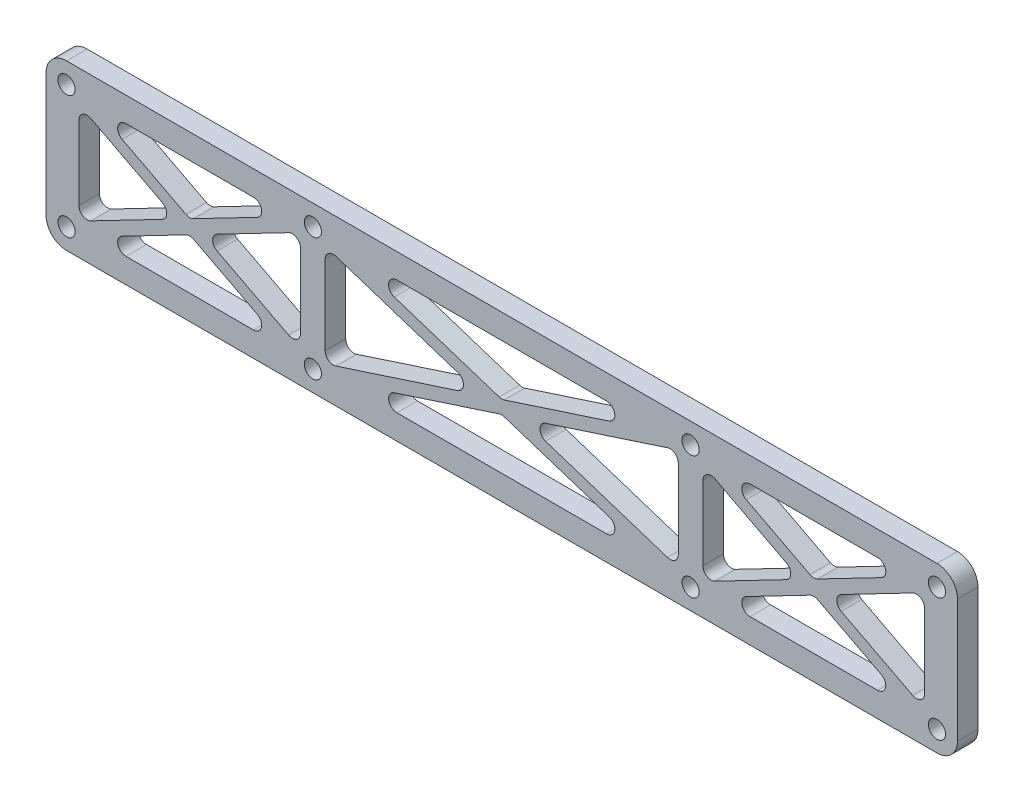
SolidWorks part; units mm, degrees
material "Thornel Mat VMA"
ref_plane "前视基准面" through (0, 0, 0) normal (0, 0, 1) x (1, 0, 0)
ref_plane "上视基准面" through (0, 0, 0) normal (0, 1, 0) x (1, 0, 0)
ref_plane "右视基准面" through (0, 0, 0) normal (1, 0, 0) x (0, 0, -1)
other "Configuration Table"
sketch "草图1" plane through (0, 0, 0) normal (0, 0, 1) x (1, 0, 0)
  line L1 (-116, -20) -> (116, -20)
  line L2 (-116, -20) -> (-116, 20)
  line L3 (-116, 20) -> (116, 20)
  line L4 (116, -20) -> (116, 20)
  line L5 (-116, -20) -> (116, 20) construction
  line L6 (-116, 20) -> (116, -20) construction
  line L7 (-46, -15) -> (46, -15) construction
  line L8 (-46, -15) -> (-46, 15) construction
  line L9 (-46, 15) -> (46, 15) construction
  line L10 (46, -15) -> (46, 15) construction
  line L11 (-46, -15) -> (46, 15) construction
  line L12 (-46, 15) -> (46, -15) construction
  circle A0 centre (-46, 15) radius 2.1
  circle A1 centre (46, 15) radius 2.1
  circle A2 centre (46, -15) radius 2.1
  circle A3 centre (-46, -15) radius 2.1
  point P0 (0, 0)
  point P5 (0, 0)
  dimension "D1" = 92
  dimension "D4" = 4.2
  dimension "D2" = 30
  dimension "D3" = 5
  dimension "D5" = 232
extrude "凸台-拉伸2" add sketch "草图1" along normal blind 5
sketch "草图3" plane through (0, 0, 5) normal (0, 0, 1) x (1, 0, 0)
  line L0 (-106, 20) -> (-106, -20) construction
  line L1 (116, 20) -> (-116, 20) construction
  line L2 (-116, -20) -> (116, -20) construction
  line L3 (106, 20) -> (106, -20) construction
  line L4 (-116, 20) -> (-116, -20) construction
  line L5 (116, -20) -> (116, 20) construction
  line L6 (0.8413, 0) -> (50000.8413, 0) construction
  line L7 (-111, 15) -> (-111, -15)
  line L8 (111, 15) -> (111, -15)
  line L9 (-106, 20) -> (106, 20)
  line L10 (-106, -20) -> (106, -20)
  circle A0 centre (-106, 15) radius 2.1
  circle A1 centre (-106, -15) radius 2.1
  circle A2 centre (106, 15) radius 2.1
  circle A3 centre (-106, 15) radius 5
  circle A4 centre (-46, 15) radius 5 construction
  circle A5 centre (-106, -15) radius 5
  circle A6 centre (106, 15) radius 5
  circle A7 centre (106, -15) radius 5
  circle A8 centre (106, -15) radius 2.1
  line M1 (116, -20) -> (116, 20)
  line M2 (116, 20) -> (-116, 20)
  line M3 (-116, 20) -> (-116, -20)
  line M4 (-116, -20) -> (116, -20)
  dimension "D3" = 4.2
  dimension "D4" = 10
  dimension "D5" = 10
  dimension "D1" = 10
  dimension "D2" = 10
extrude "切除-拉伸2" cut sketch "草图3" against normal mid plane 10 contours A5 L7 A3 M2 M3 M4 | A0 | A1 | A7 A6 L8 M4 M1 M2 | A2 | A8
sketch "草图4" plane through (0, 0, 5) normal (0, 0, 1) x (1, 0, 0)
  line L0 (0, 0) -> (50000, 0) construction
  line L1 (-43, -14) -> (43, -14)
  line L2 (-43, -14) -> (-43, 14)
  line L3 (-43, 14) -> (43, 14)
  line L4 (43, -14) -> (43, 14)
  line L5 (-43, -14) -> (43, 14) construction
  line L6 (-43, 14) -> (43, -14) construction
  line L7 (0, 0) -> (0, -50000) construction
  line L8 (-106, 15) -> (-46, 15) construction
  line L9 (-76, 15) -> (-76, 0) construction
  line L10 (106, 20) -> (-106, 20) construction
  line L11 (-103, -14) -> (-49, -14)
  line L12 (-103, -14) -> (-103, 14)
  line L13 (-103, 14) -> (-49, 14)
  line L14 (-49, -14) -> (-49, 14)
  line L15 (-103, -14) -> (-49, 14) construction
  line L16 (-103, 14) -> (-49, -14) construction
  line L17 (-111, -15) -> (-111, 15) construction
  line L18 (-102.3095, -15.3316) -> (-48.3095, 12.6684)
  line L19 (-103.6905, 12.6684) -> (-49.6905, -15.3316)
  line L20 (-43.4644, 12.5737) -> (42.5356, -15.4263)
  line L21 (-42.5356, -15.4263) -> (43.4644, 12.5737)
  line L22 (-103.6905, -12.6684) -> (-49.6905, 15.3316)
  line L23 (-102.3095, 15.3316) -> (-48.3095, -12.6684)
  line L24 (-42.5356, 15.4263) -> (43.4644, -12.5737)
  line L25 (-43.4644, -12.5737) -> (42.5356, 15.4263)
  line L26 (103, 14) -> (49, -14) construction
  line L27 (103, -14) -> (49, 14) construction
  line L28 (76, 15) -> (76, 0) construction
  line L29 (106, 15) -> (46, 15) construction
  line L30 (0, 0) -> (-50000, 0) construction
  line L31 (102.3095, 15.3316) -> (48.3095, -12.6684)
  line L32 (103.6905, -12.6684) -> (49.6905, 15.3316)
  line L33 (103.6905, 12.6684) -> (49.6905, -15.3316)
  line L34 (102.3095, -15.3316) -> (48.3095, 12.6684)
  line L35 (49, -14) -> (49, 14)
  line L36 (103, 14) -> (49, 14)
  line L37 (103, -14) -> (103, 14)
  line L38 (103, -14) -> (49, -14)
  point P0 (0, 0)
  dimension "D1" = 6
  dimension "D2" = 8
  dimension "D3" = 6
  dimension "D4" = 1.5
  dimension "D5" = 1.5
extrude "切除-拉伸4" cut sketch "草图4" against normal mid plane 10 contours L13 L23 L22 | L12 L22 L19 | L18 L23 L14 | L19 L18 L11 | L2 L25 L20 | L24 L25 L3 | L21 L24 L4 | L21 L1 L20 | L35 L31 L34 | L31 L36 L32 | L32 L37 L33 | L38 L34 L33
fillet "圆角1" radius 2 36 edges at (43, -12.4225, 2.5) (4.8452, 0, 2.5) (43, 12.4225, 2.5) (38.1548, -14, 2.5) (-38.1548, -14, 2.5) (0, -1.5775, 2.5) (72.7414, 0, 2.5) (49, -12.3103, 2.5) (49, 12.3103, 2.5) (-79.2586, 0, 2.5) (-103, -12.3103, 2.5) (-103, 12.3103, 2.5) (-49, -12.3103, 2.5) (-72.7414, 0, 2.5) (-49, 12.3103, 2.5) (-99.7414, -14, 2.5) (-76, -1.6897, 2.5) (-52.2586, -14, 2.5) (-4.8452, 0, 2.5) (-43, -12.4225, 2.5) (76, -1.6897, 2.5) (99.7414, -14, 2.5) (52.2586, -14, 2.5) (52.2586, 14, 2.5) (99.7414, 14, 2.5) (76, 1.6897, 2.5) (103, 12.3103, 2.5) (103, -12.3103, 2.5) (79.2586, 0, 2.5) (-76, 1.6897, 2.5) (-99.7414, 14, 2.5) (-52.2586, 14, 2.5) (-38.1548, 14, 2.5) (38.1548, 14, 2.5) (0, 1.5775, 2.5) (-43, 12.4225, 2.5)
